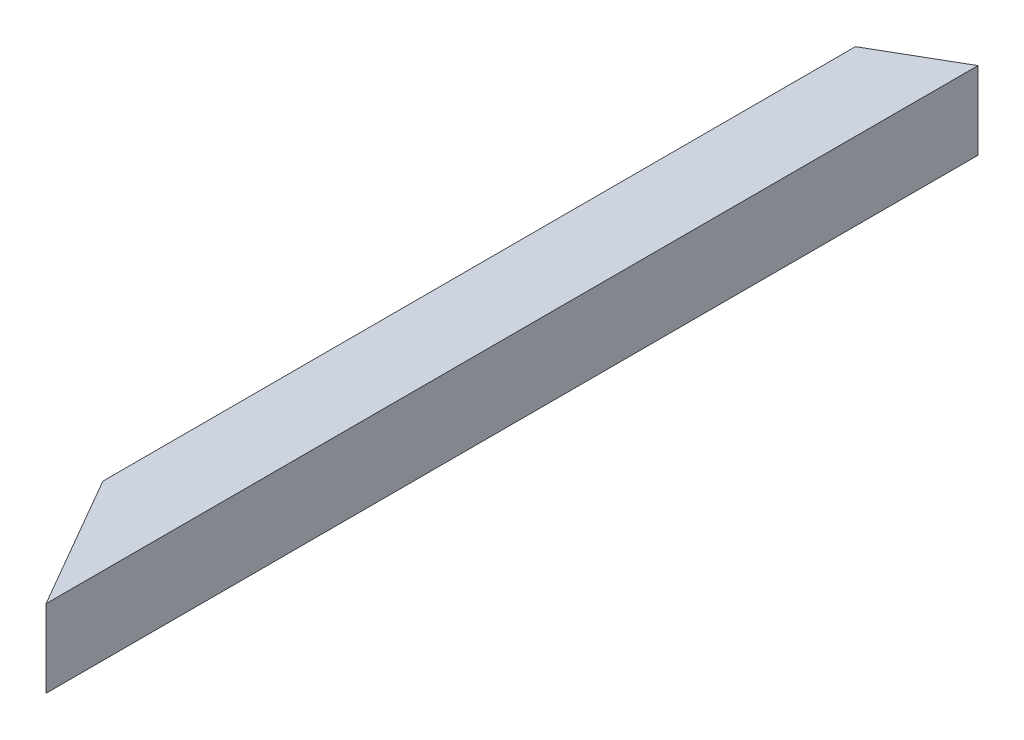
SolidWorks part; units mm, degrees
ref_plane "前视基准面" through (0, 0, 0) normal (0, 0, 1) x (1, 0, 0)
ref_plane "上视基准面" through (0, 0, 0) normal (0, 1, 0) x (1, 0, 0)
ref_plane "右视基准面" through (0, 0, 0) normal (1, 0, 0) x (0, 0, -1)
other "Configuration Table"
sketch "草图1" plane through (0, 0, 0) normal (0, 0, 1) x (1, 0, 0)
  line L1 (0, 0) -> (20, 0)
  line L2 (0, 0) -> (0, 20)
  line L3 (0, 20) -> (20, 20)
  line L4 (20, 0) -> (20, 20)
  line L5 (1, 1) -> (19, 1)
  line L6 (1, 1) -> (1, 19)
  line L7 (1, 19) -> (19, 19)
  line L8 (19, 1) -> (19, 19)
  dimension "D1" = 20
  dimension "D2" = 20
  dimension "D3" = 1
  dimension "D4" = 1
  dimension "D5" = 1
  dimension "D6" = 1
extrude "凸台-拉伸1" add sketch "草图1" along normal blind 240
sketch "草图2" plane through (0, 20, 0) normal (0, 1, 0) x (1, 0, 0)
  line L0 (20, 0) -> (0, -11.547)
  line L1 (0, -240) -> (0, 0) construction
  line L2 (0, -205.359) -> (20, -240)
  line L3 (20, 0) -> (0, 0) construction
  line L4 (0, -11.547) -> (0, 0)
  line L5 (0, 0) -> (20, 0)
  line L6 (0, -205.359) -> (0, -240)
  line L7 (0, -240) -> (20, -240)
  dimension "D1" = 90
  dimension "D2" = 30
extrude "切除-拉伸1" cut sketch "草图2" against normal blind 300
